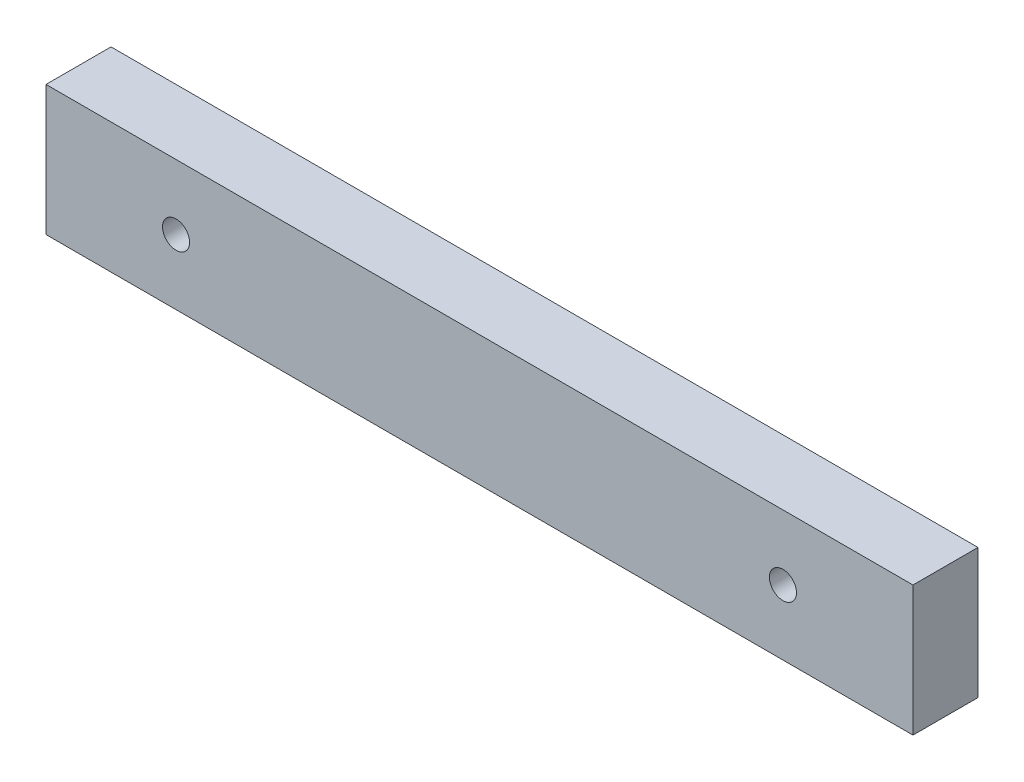
SolidWorks part; units mm, degrees
material "Pine"
ref_plane "Front Plane" through (0, 0, 0) normal (0, 0, 1) x (1, 0, 0)
ref_plane "Top Plane" through (0, 0, 0) normal (0, 1, 0) x (1, 0, 0)
ref_plane "Right Plane" through (0, 0, 0) normal (1, 0, 0) x (0, 0, -1)
sketch "Sketch1" plane through (0, 0, 0) normal (0, 0, 1) x (1, 0, 0)
  line L0 (-54.952, 6.1653) -> (199.048, 6.1653)
  line L1 (-54.952, 25.2153) -> (199.048, 25.2153)
  line L2 (-54.952, 25.2153) -> (-54.952, -12.8847)
  line L3 (-54.952, -12.8847) -> (199.048, -12.8847)
  line L4 (199.048, 25.2153) -> (199.048, -12.8847)
  line L5 (72.048, 6.1653) -> (-16.852, 6.1653)
  line L6 (72.048, 6.1653) -> (160.948, 6.1653)
  circle A0 centre (-16.852, 6.1653) radius 3.9688
  circle A1 centre (160.948, 6.1653) radius 3.9687
  dimension "D1" = 254
  dimension "D2" = 38.1
  dimension "D3" = 88.9
  dimension "D4" = 88.9
extrude "Boss-Extrude2" add sketch "Sketch1" along normal blind 19.05 contours A1 L0 L4 L1 L2 A0 L5 | A1 L0 L5 A0 L2 L3 L4
